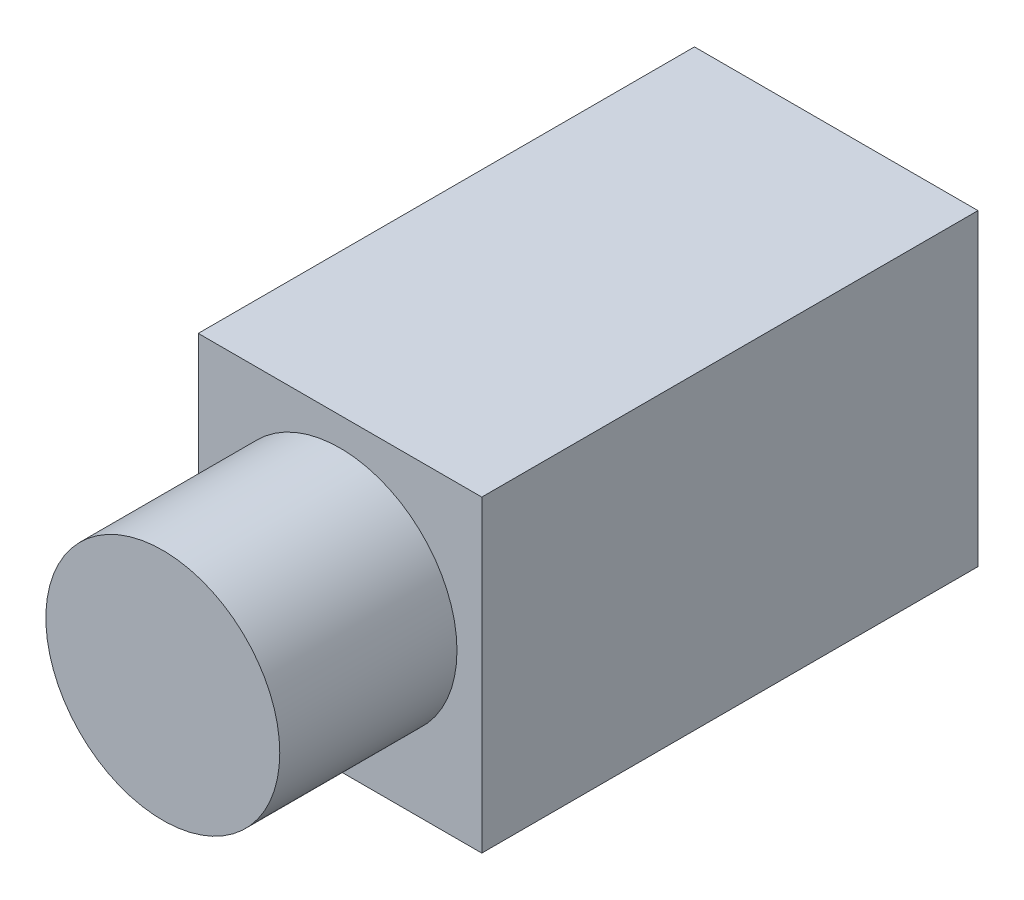
SolidWorks part; units mm, degrees
ref_plane "Front Plane" through (0, 0, 0) normal (0, 0, 1) x (1, 0, 0)
ref_plane "Top Plane" through (0, 0, 0) normal (0, 1, 0) x (1, 0, 0)
ref_plane "Right Plane" through (0, 0, 0) normal (1, 0, 0) x (0, 0, -1)
sketch "Sketch2" plane through (0, 0, 0) normal (0, 1, 0) x (1, 0, 0)
  line L1 (-20, -35) -> (20, -35)
  line L2 (-20, -35) -> (-20, 35)
  line L3 (-20, 35) -> (20, 35)
  line L4 (20, -35) -> (20, 35)
  line L5 (-20, -35) -> (20, 35) construction
  line L6 (-20, 35) -> (20, -35) construction
  point P0 (0, 0)
  dimension "D1" = 70
  dimension "D2" = 40
extrude "Boss-Extrude1" add sketch "Sketch2" along normal blind 43.5
sketch "Sketch4" plane through (0, 0, 35) normal (0, 0, 1) x (1, 0, 0)
  line L0 (-20, 0) -> (20, 0) construction
  circle A0 centre (0, 23) radius 16.5
  dimension "D2" = 33
  dimension "D1" = 23
extrude "Boss-Extrude2" add sketch "Sketch4" along normal blind 25
sketch "Sketch5" plane through (0, 0, 0) normal (0, -1, 0) x (1, 0, 0)
  line L0 (20, -35) -> (-20, -35) construction
  line L1 (-7, -20) -> (7, -20) construction
  line L2 (-7, -20) -> (-7, 25) construction
  line L3 (-7, 25) -> (7, 25) construction
  line L4 (7, -20) -> (7, 25) construction
  line L5 (-7, -20) -> (7, 25) construction
  line L6 (-7, 25) -> (7, -20) construction
  point P0 (0, 2.5)
  dimension "D1" = 15
  dimension "D2" = 45
  dimension "D3" = 14
hole_wizard "M3 Clearance Hole1" positions "Sketch6" profile "Sketch7" hole size "M3" standard "ANSI Metric"
sketch "Sketch6" plane through (0, 0, 0) normal (0, -1, 0) x (-1, 0, 0)
  point P0 (-7, 20)
  point P3 (7, 20)
  point P6 (7, -25)
  point P9 (-7, -25)
sketch "Sketch7" plane through (7, 0, -20) normal (1, 0, 0) x (0, 0, -1)
  line L0 (0, 0) -> (0, 4.1414)
  line L1 (0, 4.1414) -> (1.6, 3.18)
  line L2 (1.6, 3.18) -> (1.6, 0)
  line L5 (1.6, 0) -> (0, 0)
  line L10 (0, 4.1414) -> (-1.6, 3.18) construction
  line L11 (0, -6.35) -> (0, 107.95) construction
  dimension "Hole Dia." = 3.2
  dimension "Hole Depth" = 3.18
  dimension "Drill Angle" = 118
